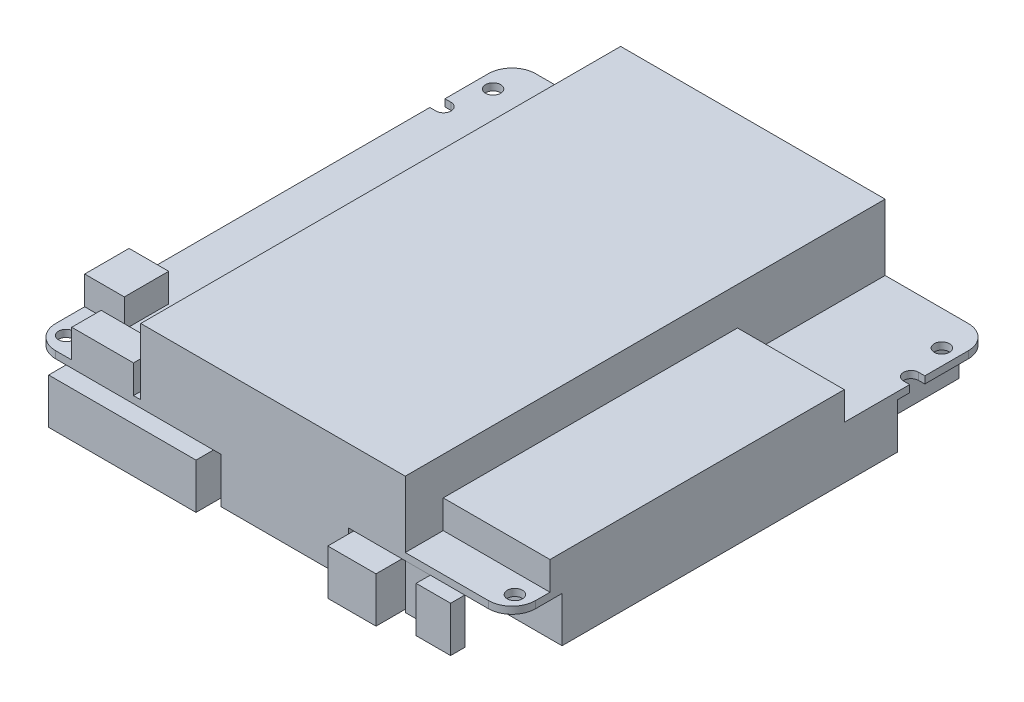
SolidWorks part; units mm, degrees
ref_plane "Спереди" through (0, 0, 0) normal (0, 0, 1) x (1, 0, 0)
ref_plane "Сверху" through (0, 0, 0) normal (0, 1, 0) x (1, 0, 0)
ref_plane "Справа" through (0, 0, 0) normal (1, 0, 0) x (0, 0, -1)
sketch "Эскиз1" plane through (0, 0, 0) normal (0, 1, 0) x (1, 0, 0)
  line L0 (-62.5901, -46.9) -> (98.0952, -46.9) construction
  line L1 (-45.8, 50.8) -> (45.8, 50.8)
  line L2 (-50.8, 45.8) -> (-50.8, -45.8)
  line L3 (-45.8, -50.8) -> (45.8, -50.8)
  line L4 (50.8, 45.8) -> (50.8, -45.8)
  line L5 (-50.8, 50.8) -> (50.8, -50.8) construction
  line L6 (-50.8, -50.8) -> (50.8, 50.8) construction
  line L7 (-47.5, 92.2985) -> (-47.5, -70.4765) construction
  line L8 (47.5, 92.2985) -> (47.5, -70.4765) construction
  line L9 (-85.2704, 43.5) -> (74.0758, 43.5) construction
  line L10 (-65.9548, 35) -> (74.0758, 35) construction
  line L11 (-49.5, 37.9623) -> (-49.5, 31.6688) construction
  line L12 (49.5, 37.9623) -> (49.5, 31.6688) construction
  line L14 (-49.5, 36.6) -> (-50.8, 36.6)
  line L16 (-49.5, 33.4) -> (-50.8, 33.4)
  line L17 (-50.8, 36.6) -> (-50.8, 33.4)
  line L18 (49.5, 36.6) -> (50.8, 36.6)
  line L20 (49.5, 33.4) -> (50.8, 33.4)
  line L21 (50.8, 36.6) -> (50.8, 33.4)
  arc A0 (45.8, 50.8) -> (50.8, 45.8) centre (45.8, 45.8) cw
  arc A1 (50.8, -45.8) -> (45.8, -50.8) centre (45.8, -45.8) cw
  arc A2 (-45.8, -50.8) -> (-50.8, -45.8) centre (-45.8, -45.8) cw
  arc A3 (-50.8, 45.8) -> (-45.8, 50.8) centre (-45.8, 45.8) cw
  circle A4 centre (-47.5, -46.9) radius 1.6
  circle A5 centre (47.5, -46.9) radius 1.6
  circle A6 centre (47.5, 43.5) radius 1.6
  circle A7 centre (-47.5, 43.5) radius 1.6
  arc A8 (-49.5, 33.4) -> (-49.5, 36.6) centre (-49.5, 35) ccw
  arc A9 (49.5, 36.6) -> (49.5, 33.4) centre (49.5, 35) ccw
  point P0 (0, 0)
  dimension "D3" = 5
  dimension "D8" = 3.2
  dimension "D9" = 8.5
  dimension "D1" = 101.6
  dimension "D2" = 101.6
  dimension "D4" = 3.3
  dimension "D5" = 95
  dimension "D6" = 7.3
  dimension "D7" = 90.4
  dimension "D10" = 1.3
  dimension "D11" = 99
extrude "Бобышка-Вытянуть1" add sketch "Эскиз1" along normal blind 1.5 contours A9 L18 L4 A0 L1 A3 L2 L14 A8 L16 A2 L3 A1 L20 A7 A6 A5 A4
sketch "Эскиз2" plane through (0, 1.5, 0) normal (0, 1, 0) x (1, 0, 0)
  line L0 (-45.8, 50.8) -> (45.8, 50.8) construction
  line L1 (-27.8, 50.8) -> (28.2, 50.8)
  line L2 (-27.8, 50.8) -> (-27.8, -50.8)
  line L3 (-27.8, -50.8) -> (28.2, -50.8)
  line L4 (28.2, 50.8) -> (28.2, -50.8)
  line L5 (-45.8, -50.8) -> (45.8, -50.8) construction
  dimension "D1" = 23
  dimension "D2" = 56
extrude "Бобышка-Вытянуть2" add sketch "Эскиз2" along normal blind 14
sketch "Эскиз3" plane through (0, 1.5, 0) normal (0, 1, 0) x (1, 0, 0)
  line L0 (28.2, -50.8) -> (28.2, 50.8) construction
  line L1 (28.2, 19.545) -> (50.8, 19.545)
  line L2 (28.2, 19.545) -> (28.2, -42.7592)
  line L3 (28.2, -42.7592) -> (50.8, -42.7592)
  line L4 (50.8, 19.545) -> (50.8, -42.7592)
  line L5 (50.8, 33.4) -> (50.8, -45.8) construction
  line L6 (-45.8, -50.8) -> (-27.8, -50.8) construction
  line L7 (-42.4088, -50.8) -> (-29.3358, -50.8)
  line L8 (-42.4088, -50.8) -> (-42.4088, -44.5816)
  line L9 (-42.4088, -44.5816) -> (-29.3358, -44.5816)
  line L10 (-29.3358, -50.8) -> (-29.3358, -44.5816)
  line L11 (-50.8, 33.4) -> (-50.8, -45.8) construction
  line L12 (-50.8, -39.6706) -> (-42.4088, -39.6706)
  line L13 (-50.8, -39.6706) -> (-50.8, -30.2711)
  line L14 (-50.8, -30.2711) -> (-42.4088, -30.2711)
  line L15 (-42.4088, -39.6706) -> (-42.4088, -30.2711)
extrude "Бобышка-Вытянуть3" add sketch "Эскиз3" along normal blind 6
sketch "Эскиз4" plane through (0, 0, 0) normal (0, -1, 0) x (1, 0, 0)
  line L0 (-45.8, -50.8) -> (45.8, -50.8) construction
  line L1 (30.8, -50.8) -> (24.8, -50.8)
  line L2 (30.8, -50.8) -> (30.8, -39.5)
  line L3 (30.8, -39.5) -> (24.8, -39.5)
  line L4 (24.8, -50.8) -> (24.8, -39.5)
  line L5 (50.8, -45.8) -> (50.8, -36.6) construction
  dimension "D1" = 20
  dimension "D2" = 11.3
  dimension "D3" = 6
extrude "Бобышка-Вытянуть4" add sketch "Эскиз4" along normal blind 13.4
sketch "Эскиз5" plane through (0, 0, -50.8) normal (0, 0, -1) x (-1, 0, 0)
  line L0 (-28.2, 15.5) -> (27.8, 15.5) construction
  line L1 (-27.4063, 15.4) -> (-25.6563, 15.4)
  line L2 (-27.4063, 15.4) -> (-27.4063, 7.4)
  line L3 (-27.4063, 7.4) -> (-25.6563, 7.4)
  line L4 (-25.6563, 15.4) -> (-25.6563, 7.4)
  line L5 (-25.4563, 15.4) -> (-23.7063, 15.4)
  line L6 (-25.4563, 15.4) -> (-25.4563, 7.4)
  line L7 (-25.4563, 7.4) -> (-23.7063, 7.4)
  line L8 (-23.7063, 15.4) -> (-23.7063, 7.4)
  line L9 (-23.5063, 15.4) -> (-21.7563, 15.4)
  line L10 (-23.5063, 15.4) -> (-23.5063, 7.4)
  line L11 (-23.5063, 7.4) -> (-21.7563, 7.4)
  line L12 (-21.7563, 15.4) -> (-21.7563, 7.4)
  line L13 (-21.5563, 15.4) -> (-19.8063, 15.4)
  line L14 (-21.5563, 15.4) -> (-21.5563, 7.4)
  line L15 (-21.5563, 7.4) -> (-19.8063, 7.4)
  line L16 (-19.8063, 15.4) -> (-19.8063, 7.4)
  line L17 (-19.6063, 15.4) -> (-17.8563, 15.4)
  line L18 (-19.6063, 15.4) -> (-19.6063, 7.4)
  line L19 (-19.6063, 7.4) -> (-17.8563, 7.4)
  line L20 (-17.8563, 15.4) -> (-17.8563, 7.4)
  line L21 (-17.6563, 15.4) -> (-15.9063, 15.4)
  line L22 (-17.6563, 15.4) -> (-17.6563, 7.4)
  line L23 (-17.6563, 7.4) -> (-15.9063, 7.4)
  line L24 (-15.9063, 15.4) -> (-15.9063, 7.4)
  line L25 (-15.7063, 15.4) -> (-13.9563, 15.4)
  line L26 (-15.7063, 15.4) -> (-15.7063, 7.4)
  line L27 (-15.7063, 7.4) -> (-13.9563, 7.4)
  line L28 (-13.9563, 15.4) -> (-13.9563, 7.4)
  line L29 (-13.7563, 15.4) -> (-12.0063, 15.4)
  line L30 (-13.7563, 15.4) -> (-13.7563, 7.4)
  line L31 (-13.7563, 7.4) -> (-12.0063, 7.4)
  line L32 (-12.0063, 15.4) -> (-12.0063, 7.4)
  line L33 (-11.8063, 15.4) -> (-10.0563, 15.4)
  line L34 (-11.8063, 15.4) -> (-11.8063, 7.4)
  line L35 (-11.8063, 7.4) -> (-10.0563, 7.4)
  line L36 (-10.0563, 15.4) -> (-10.0563, 7.4)
  line L37 (-9.8563, 15.4) -> (-8.1063, 15.4)
  line L38 (-9.8563, 15.4) -> (-9.8563, 7.4)
  line L39 (-9.8563, 7.4) -> (-8.1063, 7.4)
  line L40 (-8.1063, 15.4) -> (-8.1063, 7.4)
  line L41 (-7.9063, 15.4) -> (-6.1563, 15.4)
  line L42 (-7.9063, 15.4) -> (-7.9063, 7.4)
  line L43 (-7.9063, 7.4) -> (-6.1563, 7.4)
  line L44 (-6.1563, 15.4) -> (-6.1563, 7.4)
  line L45 (-5.9563, 15.4) -> (-4.2063, 15.4)
  line L46 (-5.9563, 15.4) -> (-5.9563, 7.4)
  line L47 (-5.9563, 7.4) -> (-4.2063, 7.4)
  line L48 (-4.2063, 15.4) -> (-4.2063, 7.4)
  line L49 (-4.0063, 15.4) -> (-2.2563, 15.4)
  line L50 (-4.0063, 15.4) -> (-4.0063, 7.4)
  line L51 (-4.0063, 7.4) -> (-2.2563, 7.4)
  line L52 (-2.2563, 15.4) -> (-2.2563, 7.4)
  line L53 (-2.0563, 15.4) -> (-0.3063, 15.4)
  line L54 (-2.0563, 15.4) -> (-2.0563, 7.4)
  line L55 (-2.0563, 7.4) -> (-0.3063, 7.4)
  line L56 (-0.3063, 15.4) -> (-0.3063, 7.4)
  line L57 (-0.1063, 15.4) -> (1.6437, 15.4)
  line L58 (-0.1063, 15.4) -> (-0.1063, 7.4)
  line L59 (-0.1063, 7.4) -> (1.6437, 7.4)
  line L60 (1.6437, 15.4) -> (1.6437, 7.4)
  line L61 (1.8437, 15.4) -> (3.5937, 15.4)
  line L62 (1.8437, 15.4) -> (1.8437, 7.4)
  line L63 (1.8437, 7.4) -> (3.5937, 7.4)
  line L64 (3.5937, 15.4) -> (3.5937, 7.4)
  line L65 (3.7937, 15.4) -> (5.5437, 15.4)
  line L66 (3.7937, 15.4) -> (3.7937, 7.4)
  line L67 (3.7937, 7.4) -> (5.5437, 7.4)
  line L68 (5.5437, 15.4) -> (5.5437, 7.4)
  line L69 (5.7437, 15.4) -> (7.4937, 15.4)
  line L70 (5.7437, 15.4) -> (5.7437, 7.4)
  line L71 (5.7437, 7.4) -> (7.4937, 7.4)
  line L72 (7.4937, 15.4) -> (7.4937, 7.4)
  line L73 (7.6937, 15.4) -> (9.4437, 15.4)
  line L74 (7.6937, 15.4) -> (7.6937, 7.4)
  line L75 (7.6937, 7.4) -> (9.4437, 7.4)
  line L76 (9.4437, 15.4) -> (9.4437, 7.4)
  line L77 (9.6437, 15.4) -> (11.3937, 15.4)
  line L78 (9.6437, 15.4) -> (9.6437, 7.4)
  line L79 (9.6437, 7.4) -> (11.3937, 7.4)
  line L80 (11.3937, 15.4) -> (11.3937, 7.4)
  line L81 (11.5937, 15.4) -> (13.3437, 15.4)
  line L82 (11.5937, 15.4) -> (11.5937, 7.4)
  line L83 (11.5937, 7.4) -> (13.3437, 7.4)
  line L84 (13.3437, 15.4) -> (13.3437, 7.4)
  line L85 (13.5437, 15.4) -> (15.2937, 15.4)
  line L86 (13.5437, 15.4) -> (13.5437, 7.4)
  line L87 (13.5437, 7.4) -> (15.2937, 7.4)
  line L88 (15.2937, 15.4) -> (15.2937, 7.4)
  line L89 (15.4937, 15.4) -> (17.2437, 15.4)
  line L90 (15.4937, 15.4) -> (15.4937, 7.4)
  line L91 (15.4937, 7.4) -> (17.2437, 7.4)
  line L92 (17.2437, 15.4) -> (17.2437, 7.4)
  line L93 (17.4437, 15.4) -> (19.1937, 15.4)
  line L94 (17.4437, 15.4) -> (17.4437, 7.4)
  line L95 (17.4437, 7.4) -> (19.1937, 7.4)
  line L96 (19.1937, 15.4) -> (19.1937, 7.4)
  line L97 (19.3937, 15.4) -> (21.1437, 15.4)
  line L98 (19.3937, 15.4) -> (19.3937, 7.4)
  line L99 (19.3937, 7.4) -> (21.1437, 7.4)
  line L100 (21.1437, 15.4) -> (21.1437, 7.4)
  line L101 (21.3437, 15.4) -> (23.0937, 15.4)
  line L102 (21.3437, 15.4) -> (21.3437, 7.4)
  line L103 (21.3437, 7.4) -> (23.0937, 7.4)
  line L104 (23.0937, 15.4) -> (23.0937, 7.4)
  line L105 (23.2937, 15.4) -> (25.0437, 15.4)
  line L106 (23.2937, 15.4) -> (23.2937, 7.4)
  line L107 (23.2937, 7.4) -> (25.0437, 7.4)
  line L108 (25.0437, 15.4) -> (25.0437, 7.4)
  line L109 (25.2437, 15.4) -> (26.9937, 15.4)
  line L110 (25.2437, 15.4) -> (25.2437, 7.4)
  line L111 (25.2437, 7.4) -> (26.9937, 7.4)
  line L112 (26.9937, 15.4) -> (26.9937, 7.4)
  dimension "D1" = 1.75
  dimension "D2" = 8
  dimension "D3" = 0.1
  dimension "D4" = 0.8
  dimension "D5" = 28
extrude "Вырез-Вытянуть1" cut sketch "Эскиз5" against normal blind 45
sketch "Эскиз6" plane through (0, 0, 0) normal (0, -1, 0) x (1, 0, 0)
  line L0 (30.8, -50.8) -> (45.8, -50.8) construction
  line L1 (43.8, -50.8) -> (16.8, -50.8)
  line L2 (43.8, -50.8) -> (43.8, -37.8)
  line L3 (43.8, -37.8) -> (16.8, -37.8)
  line L4 (16.8, -50.8) -> (16.8, -37.8)
  line L5 (50.8, -45.8) -> (50.8, -36.6) construction
  line L6 (-45.8, -50.8) -> (24.8, -50.8) construction
  line L7 (-41.8, -50.8) -> (-5.8, -50.8)
  line L8 (-41.8, -50.8) -> (-41.8, -26.8)
  line L9 (-41.8, -26.8) -> (-5.8, -26.8)
  line L10 (-5.8, -50.8) -> (-5.8, -26.8)
  line L11 (-50.8, -45.8) -> (-50.8, -36.6) construction
  line L12 (-50.8, -33.4) -> (-50.8, 45.8) construction
  line L13 (-50.8, -22.8) -> (-20.8, -22.8)
  line L14 (-50.8, -22.8) -> (-50.8, 32.2)
  line L15 (-50.8, 32.2) -> (-20.8, 32.2)
  line L16 (-20.8, -22.8) -> (-20.8, 32.2)
  line L17 (50.8, -33.4) -> (50.8, 45.8) construction
  line L18 (50.8, -30.8) -> (-0.2, -30.8)
  line L19 (50.8, -30.8) -> (50.8, 40.2)
  line L20 (50.8, 40.2) -> (-0.2, 40.2)
  line L21 (-0.2, -30.8) -> (-0.2, 40.2)
  line L22 (-45.8, 50.8) -> (45.8, 50.8) construction
  line L23 (-43.6, 37.5) -> (-12.4, 37.5)
  line L24 (-43.6, 37.5) -> (-43.6, 54.5)
  line L25 (-43.6, 54.5) -> (-12.4, 54.5)
  line L26 (-12.4, 37.5) -> (-12.4, 54.5)
  line L28 (-3.8, 24.8) -> (-10.16, 24.8)
  line L29 (-3.8, 24.8) -> (-3.8, 40.8)
  line L30 (-3.8, 40.8) -> (-10.16, 40.8)
  line L31 (-10.16, 24.8) -> (-10.16, 40.8)
  line L32 (-10.8, 50.8) -> (16.2, 50.8)
  line L33 (-10.8, 50.8) -> (-10.8, 46.8)
  line L34 (-10.8, 46.8) -> (16.2, 46.8)
  line L35 (16.2, 50.8) -> (16.2, 46.8)
  line L36 (27.51, 42.8) -> (17.3, 42.8)
  line L37 (27.51, 42.8) -> (27.51, 56.3)
  line L38 (27.51, 56.3) -> (17.3, 56.3)
  line L39 (17.3, 42.8) -> (17.3, 56.3)
  line L40 (35.8, 48.2) -> (28.2, 48.2)
  line L41 (35.8, 48.2) -> (35.8, 50.7)
  line L42 (35.8, 50.7) -> (28.2, 50.7)
  line L43 (28.2, 48.2) -> (28.2, 50.7)
  line L44 (40.8, 50.8) -> (33.5, 50.8)
  line L45 (40.8, 50.8) -> (40.8, 53.8)
  line L46 (40.8, 53.8) -> (33.5, 53.8)
  line L47 (33.5, 50.8) -> (33.5, 53.8)
  point P57 (16.8882, 53.9396)
  point P58 (17.8701, 52.2979)
  dimension "D1" = 7
  dimension "D2" = 27
  dimension "D3" = 13
  dimension "D4" = 9
  dimension "D5" = 36
  dimension "D6" = 24
  dimension "D7" = 28
  dimension "D8" = 55
  dimension "D9" = 30
  dimension "D10" = 51
  dimension "D11" = 20
  dimension "D12" = 71
  dimension "D13" = 7.2
  dimension "D14" = 31.2
  dimension "D15" = 3.7
  dimension "D16" = 17
  dimension "D17" = 16
  dimension "D18" = 6.36
  dimension "D19" = 26
  dimension "D20" = 47
  dimension "D21" = 27
  dimension "D22" = 4
  dimension "D23" = 40
  dimension "D24" = 3
  dimension "D25" = 7.3
  dimension "D26" = 10
  dimension "D27" = 0
  dimension "D28" = 7.6
  dimension "D29" = 2.5
  dimension "D30" = 0.1
  dimension "D31" = 15
  dimension "D32" = 33.5
  dimension "D33" = 10.21
  dimension "D34" = 13.5
  dimension "D35" = 5.5
extrude "Бобышка-Вытянуть5" add sketch "Эскиз6" along normal blind 9.6
